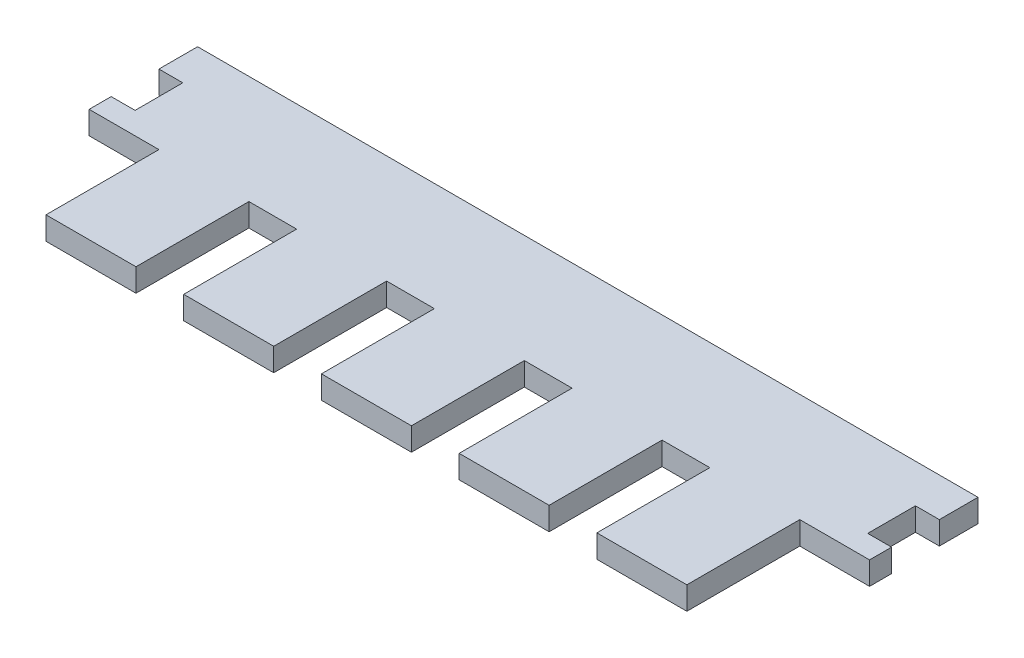
SolidWorks part; units mm, degrees
ref_plane "Front Plane" through (0, 0, 0) normal (0, 0, 1) x (1, 0, 0)
ref_plane "Top Plane" through (0, 0, 0) normal (0, 1, 0) x (1, 0, 0)
ref_plane "Right Plane" through (0, 0, 0) normal (1, 0, 0) x (0, 0, -1)
sketch "Sketch1" plane through (0, 0, 0) normal (0, 1, 0) x (1, 0, 0)
  line L2 (-107.95, -28.575) -> (-107.95, 28.575)
  line L3 (-107.95, 28.575) -> (107.95, 28.575)
  line L4 (107.95, -28.575) -> (107.95, 28.575)
  line L5 (-107.95, -28.575) -> (107.95, 28.575) construction
  line L6 (-107.95, 28.575) -> (107.95, -28.575) construction
  line L11 (-107.95, -28.575) -> (107.95, -28.575)
  point P0 (0, 0)
  dimension "D1" = 57.15
  dimension "D2" = 215.9
extrude "Boss-Extrude1" add sketch "Sketch1" along normal blind 6.35
sketch "Sketch3" plane through (0, 0, 0) normal (0, 1, 0) x (1, 0, 0)
  line L0 (-107.95, -28.575) -> (107.95, -28.575) construction
  line L1 (-88.646, -28.575) -> (-88.646, -59.817)
  line L2 (-88.646, -59.817) -> (-63.754, -59.817)
  line L3 (-63.754, -59.817) -> (-63.754, -28.575)
  line L4 (-63.754, -28.575) -> (-88.646, -28.575)
  line L5 (-50.546, -28.575) -> (-50.546, -59.817)
  line L6 (-50.546, -59.817) -> (-25.654, -59.817)
  line L7 (-25.654, -59.817) -> (-25.654, -28.575)
  line L8 (-25.654, -28.575) -> (-50.546, -28.575)
  line L9 (-12.446, -28.575) -> (-12.446, -59.817)
  line L10 (-12.446, -59.817) -> (12.446, -59.817)
  line L11 (12.446, -59.817) -> (12.446, -28.575)
  line L12 (12.446, -28.575) -> (-12.446, -28.575)
  line L25 (25.654, -28.575) -> (25.654, -59.817) [skipped]
  line L26 (25.654, -59.817) -> (50.546, -59.817) [skipped]
  line L27 (50.546, -59.817) -> (50.546, -28.575) [skipped]
  line L28 (50.546, -28.575) -> (25.654, -28.575) [skipped]
  line L29 (63.754, -28.575) -> (63.754, -59.817) [skipped]
  line L30 (63.754, -59.817) -> (88.646, -59.817) [skipped]
  line L31 (88.646, -59.817) -> (88.646, -28.575) [skipped]
  line L32 (88.646, -28.575) -> (63.754, -28.575) [skipped]
  line L33 (101.854, -28.575) -> (101.854, -59.817) [skipped]
  line L34 (101.854, -59.817) -> (126.746, -59.817) [skipped]
  line L35 (126.746, -59.817) -> (126.746, -28.575) [skipped]
  line L36 (126.746, -28.575) -> (101.854, -28.575) [skipped]
  line L37 (25.654, -28.575) -> (25.654, -59.817)
  line L38 (25.654, -59.817) -> (50.546, -59.817)
  line L39 (50.546, -59.817) -> (50.546, -28.575)
  line L40 (50.546, -28.575) -> (25.654, -28.575)
  line L41 (63.754, -28.575) -> (63.754, -59.817)
  line L42 (63.754, -59.817) -> (88.646, -59.817)
  line L43 (88.646, -59.817) -> (88.646, -28.575)
  line L44 (88.646, -28.575) -> (63.754, -28.575)
  point P0 (-76.2, -28.575)
  point P6 (-38.1, -28.575)
  point P8 (114.3, -28.575)
  point P14 (0, -28.575)
  point P20 (76.2, -28.575)
  point P21 (38.1, -28.575)
  point P22 (38.1, -28.575)
  point P27 (76.2, -28.575)
  dimension "D1" = 24.892
  dimension "D2" = 31.242
  dimension "D3" = 31.75
  dimension "D5" = 38.1
  dimension "D4" = 6
  dimension "D6" = 3
extrude "Boss-Extrude2" add sketch "Sketch3" along normal blind 6.35
sketch "Sketch4" plane through (0, 0, 0) normal (0, 1, 0) x (1, 0, 0)
  line L0 (-107.95, 28.575) -> (-107.95, -28.575) construction
  line L1 (107.95, 28.575) -> (-107.95, 28.575) construction
  line L2 (-114.554, 16.129) -> (-101.346, 16.129)
  line L3 (-114.554, 16.129) -> (-114.554, 2.921)
  line L4 (-114.554, 2.921) -> (-101.346, 2.921)
  line L5 (-101.346, 16.129) -> (-101.346, 2.921)
  line L6 (-114.554, 16.129) -> (-101.346, 2.921) construction
  line L7 (-114.554, 2.921) -> (-101.346, 16.129) construction
  line L8 (0, 0) -> (0, 63.6475) construction
  line L9 (-114.554, -9.271) -> (-101.346, -9.271)
  line L10 (-101.346, -9.271) -> (-101.346, -22.479)
  line L11 (-114.554, -22.479) -> (-101.346, -22.479)
  line L12 (-114.554, -9.271) -> (-114.554, -22.479)
  line L13 (114.554, 2.921) -> (101.346, 16.129) construction
  line L14 (114.554, 16.129) -> (101.346, 2.921) construction
  line L15 (114.554, -9.271) -> (114.554, -22.479)
  line L16 (114.554, -22.479) -> (101.346, -22.479)
  line L17 (101.346, -9.271) -> (101.346, -22.479)
  line L18 (114.554, -9.271) -> (101.346, -9.271)
  line L19 (101.346, 16.129) -> (101.346, 2.921)
  line L20 (114.554, 2.921) -> (101.346, 2.921)
  line L21 (114.554, 16.129) -> (114.554, 2.921)
  line L22 (114.554, 16.129) -> (101.346, 16.129)
  point P0 (-107.95, 9.525)
  point P1 (-107.95, 9.525)
  point P25 (107.95, 9.525)
  dimension "D1" = 13.208
  dimension "D2" = 13.208
  dimension "D3" = 19.05
  dimension "D5" = 2
extrude "Cut-Extrude2" cut sketch "Sketch4" along normal through all
sketch "Sketch5" plane through (0, 6.35, 0) normal (0, 1, 0) x (1, 0, 0)
  line L1 (-107.95, 28.575) -> (171.8176, 28.575)
  line L2 (-107.95, 28.575) -> (-107.95, 15.875)
  line L3 (-107.95, 15.875) -> (171.8176, 15.875)
  line L4 (171.8176, 28.575) -> (171.8176, 15.875)
  dimension "D1" = 12.7
extrude "Cut-Extrude3" cut sketch "Sketch5" against normal through all
sketch "Sketch6" plane through (0, 6.35, 0) normal (0, 1, 0) x (1, 0, 0)
  line L1 (-107.95, 15.875) -> (107.95, 15.875)
  line L2 (-107.95, 15.875) -> (-107.95, 1.425)
  line L3 (-107.95, 1.425) -> (107.95, 1.425)
  line L4 (107.95, 15.875) -> (107.95, 1.425)
  line L5 (-63.754, -28.575) -> (-50.546, -28.575) construction
  line L6 (107.95, -9.271) -> (107.95, 2.921) construction
  line L7 (-107.95, 2.921) -> (-107.95, -9.271) construction
  line L8 (-101.346, 15.875) -> (101.346, 15.875) construction
  dimension "D1" = 30
extrude "Cut-Extrude4" cut sketch "Sketch6" against normal through all
